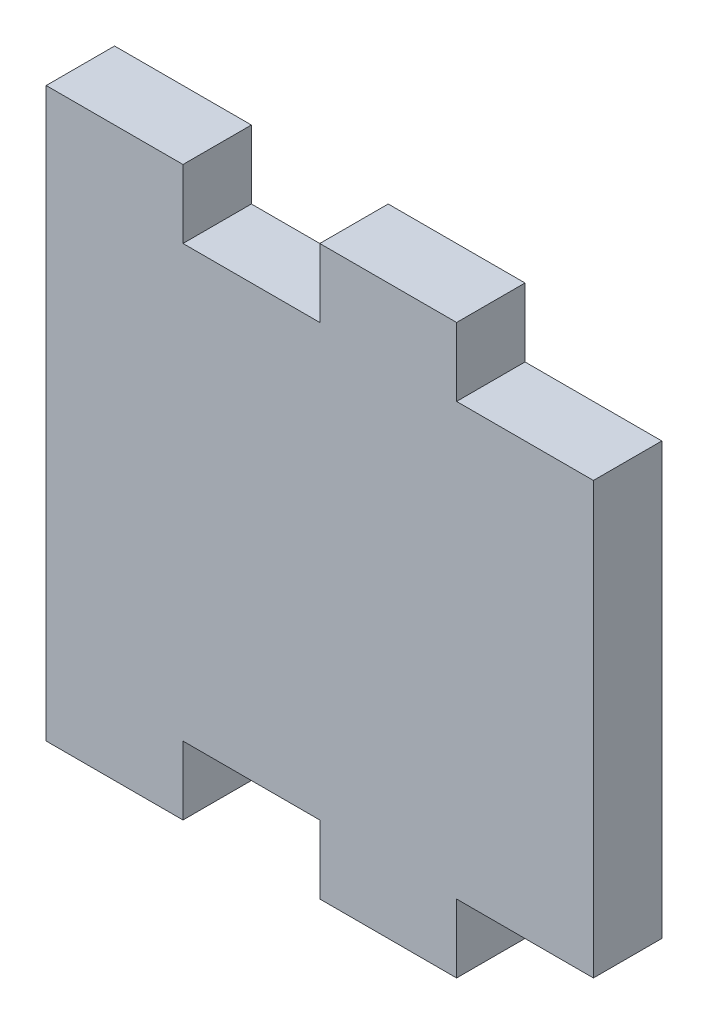
SolidWorks part; units mm, degrees
material "Acrylic (Medium-high impact)"
ref_plane "Front Plane" through (0, 0, 0) normal (0, 0, 1) x (1, 0, 0)
ref_plane "Top Plane" through (0, 0, 0) normal (0, 1, 0) x (1, 0, 0)
ref_plane "Right Plane" through (0, 0, 0) normal (1, 0, 0) x (0, 0, -1)
sketch "Sketch1" plane through (0, 0, 0) normal (0, 0, 1) x (1, 0, 0)
  line L0 (0, 0) -> (0, -3.175)
  line L1 (6.35, 0) -> (12.7, 0)
  line L2 (0, 0) -> (0, 20)
  line L3 (6.35, 20) -> (12.7, 20)
  line L4 (25.4, 0) -> (25.4, 20)
  line L5 (0, -3.175) -> (6.35, -3.175)
  line L6 (6.35, -3.175) -> (6.35, 0)
  line L7 (12.7, 0) -> (12.7, -3.175)
  line L8 (12.7, -3.175) -> (19.05, -3.175)
  line L9 (19.05, -3.175) -> (19.05, 0)
  line L10 (19.05, 0) -> (25.4, 0)
  line L11 (0, 10) -> (25.4, 10) construction
  line L12 (19.05, 23.175) -> (19.05, 20)
  line L13 (12.7, 23.175) -> (19.05, 23.175)
  line L14 (12.7, 20) -> (12.7, 23.175)
  line L15 (6.35, 23.175) -> (6.35, 20)
  line L16 (0, 23.175) -> (6.35, 23.175)
  line L17 (0, 20) -> (0, 23.175)
  line L18 (19.05, 20) -> (25.4, 20)
  dimension "D1" = 6.35
  dimension "D2" = 3.175
  dimension "D3" = 20
extrude "Boss-Extrude1" add sketch "Sketch1" along normal blind 3.175
